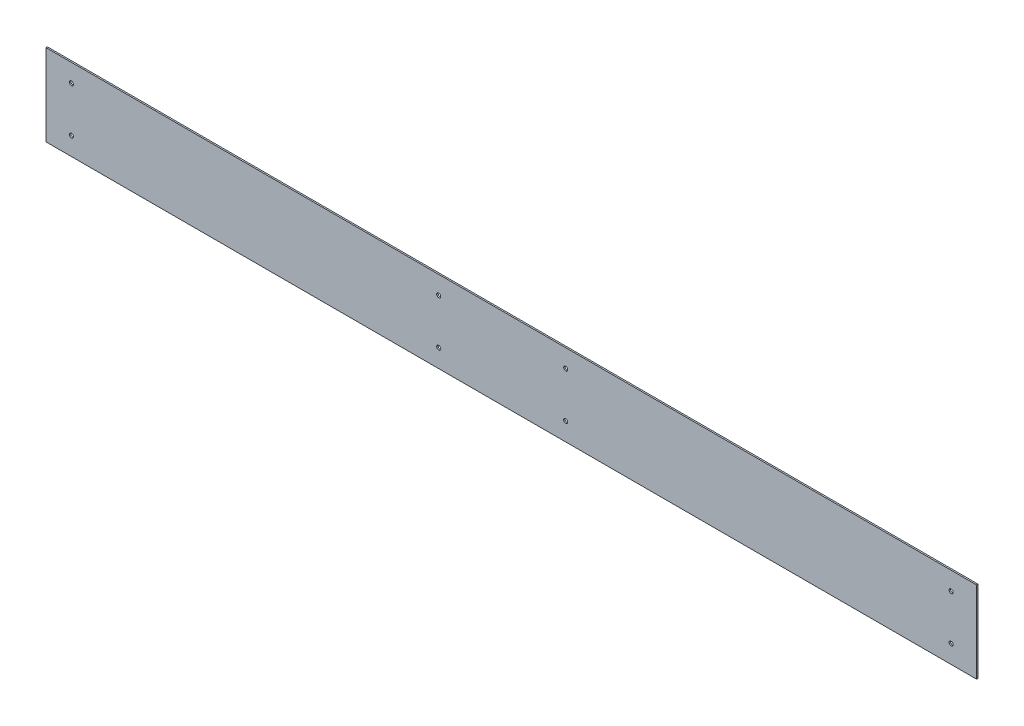
SolidWorks part; units mm, degrees
ref_plane "Front Plane" through (0, 0, 0) normal (0, 0, 1) x (1, 0, 0)
ref_plane "Top Plane" through (0, 0, 0) normal (0, 1, 0) x (1, 0, 0)
ref_plane "Right Plane" through (0, 0, 0) normal (1, 0, 0) x (0, 0, -1)
sketch "Sketch1" plane through (0, 0, 0) normal (0, 0, 1) x (1, 0, 0)
  line L1 (-513, -45) -> (513, -45)
  line L2 (-513, -45) -> (-513, 45)
  line L3 (-513, 45) -> (513, 45)
  line L4 (513, -45) -> (513, 45)
  line L5 (-513, -45) -> (513, 45) construction
  line L6 (-513, 45) -> (513, -45) construction
  point P0 (0, 0)
  dimension "D1" = 1026
  dimension "D2" = 90
extrude "Boss-Extrude1" add sketch "Sketch1" along normal blind 1.5875
hole_wizard "M4 Clearance Hole1" positions "Sketch2" profile "Sketch4" hole size "M4" standard "ANSI Metric" end condition through all
sketch "Sketch2" plane through (0, 0, 1.5875) normal (0, 0, 1) x (1, 0, 0)
  line L0 (-485, 25) -> (-485, -25)
  line L1 (513, 45) -> (-513, 45) construction
  line L2 (-513, -45) -> (513, -45) construction
  line L3 (-513, 45) -> (-513, -45) construction
  line L4 (0, -0.8731) -> (0, 0.8731) construction
  line L5 (485, 25) -> (485, -25)
  line L6 (-80, 25) -> (-80, -25)
  line L8 (60, 25) -> (60, -25)
  point P1 (-485, 25)
  point P2 (-485, -25)
  point P19 (485, -25)
  point P20 (485, 25)
  point P24 (-80, 25)
  point P25 (-80, -25)
  point P28 (60, 25)
  point P29 (60, -25)
  dimension "D1" = 20
  dimension "D2" = 20
  dimension "D3" = 28
  dimension "D4" = 433
  dimension "D5" = 140
sketch "Sketch4" plane through (-485, 25, 1.5875) normal (1, 0, 0) x (0, -1, 0)
  line L0 (0, 0) -> (0, 1.5875)
  line L1 (0, 1.5875) -> (2.25, 1.5875)
  line L2 (2.25, 1.5875) -> (2.25, 0)
  line L5 (2.25, 0) -> (0, 0)
  line L11 (0, -6.35) -> (0, 107.95) construction
  dimension "Thru Hole Dia." = 4.5
  dimension "Thru Hole Depth" = 1.5875
